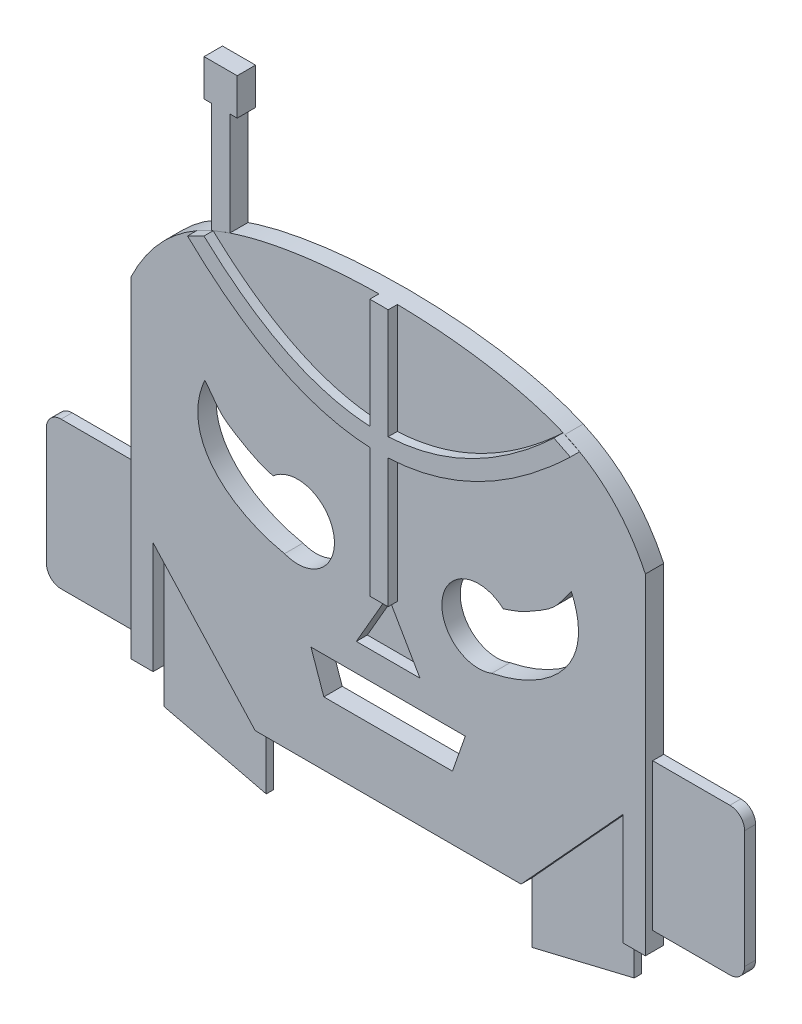
SolidWorks part; units mm, degrees
ref_plane "Alzado" through (0, 0, 0) normal (0, 0, 1) x (1, 0, 0)
ref_plane "Planta" through (0, 0, 0) normal (0, 1, 0) x (1, 0, 0)
ref_plane "Vista lateral" through (0, 0, 0) normal (1, 0, 0) x (0, 0, -1)
sketch "Croquis1" plane through (0, 0, 0) normal (0, 0, 1) x (1, 0, 0)
  line L0 (0, 0) -> (0, -7.1549) construction
  line L1 (-4.5362, -0.3549) -> (0, -0.3549) construction
  line L3 (-7, -2.6549) -> (-7, -11.6549)
  line L4 (-7, -11.6549) -> (7, -11.6549)
  line L5 (7, -2.6549) -> (7, -11.6549)
  line L6 (-7, -2.6549) -> (7, -11.6549) construction
  line L7 (-7, -11.6549) -> (7, -2.6549) construction
  line L12 (0, -0.3549) -> (4.5362, -0.3549) construction
  line L14 (-9.1, -7.1549) -> (-7, -7.1549)
  line L15 (-9.5, -7.5549) -> (-9.5, -10.7549)
  line L16 (-9.1, -11.1549) -> (-7, -11.1549)
  line L17 (-7, -7.1549) -> (-7, -11.1549)
  line L18 (-9.5, -7.1549) -> (-7, -11.1549) construction
  line L19 (-9.5, -11.1549) -> (-7, -7.1549) construction
  arc A0 (-9.5, -10.7549) -> (-9.1, -11.1549) centre (-9.1, -10.7549) ccw
  arc A1 (-9.1, -7.1549) -> (-9.5, -7.5549) centre (-9.1, -7.5549) ccw
  ellipse E0 centre (0, -1.6549) end of major axis (6.017, -1.6549) minor radius 1.9787 (5.4935, -0.8477) -> (-5.46, -0.8234) ccw
  spline S0 degree 2 poles (-7, -2.6549) (-6.1937, -0.9682) (-4.5362, -0.3549) knots 0 0 0 1 1 1
  spline S1 degree 2 poles (7, -2.6549) (6.1948, -0.9725) (4.5362, -0.3549) knots 0 0 0 1 1 1
  point P7 (8.2607, -8.8714)
  point P12 (-8.25, -9.1549)
  dimension "D2" = 0.4
  dimension "D7" = 3.4606
  dimension "D8" = 3.46
  dimension "D1" = 14
  dimension "D3" = 4
  dimension "D4" = 6.8
  dimension "D5" = 4.5362
  dimension "D6" = 5.5
  dimension "D9" = 0.5
  dimension "D10" = 2.5
  dimension "D11" = 9
extrude "Saliente-Extruir1" add sketch "Croquis1" along normal blind 0.5 contours L5 S1 E0 S0 L3 L4 | L14 A1 L15 A0 L16 L3
sketch "Croquis2" plane through (0, 0, 0.5) normal (0, 0, 1) x (1, 0, 0)
  line L0 (0, 0) -> (0, -3.1762) construction
  line L1 (-0.25, -6.6762) -> (0.25, -6.6762)
  line L2 (-0.25, -6.6762) -> (-0.25, 0.3238)
  line L3 (-0.25, 0.3238) -> (0.25, 0.3238)
  line L4 (0.25, -6.6762) -> (0.25, 0.3238)
  line L5 (-0.25, -6.6762) -> (0.25, 0.3238) construction
  line L6 (-0.25, 0.3238) -> (0.25, -6.6762) construction
  line L7 (-5.2093, -0.6681) -> (-4.7616, -0.4455) construction
  line L8 (0, -2.6762) -> (0, -3.1762) construction
  line L9 (4.7616, -0.4455) -> (5.2088, -0.6691) construction
  line L10 (-5.2093, -0.6681) -> (-4.7616, -0.4455)
  line L11 (4.7616, -0.4455) -> (5.2088, -0.6691)
  line L12 (-4.7616, -0.4455) -> (0, -0.4455) construction
  line L13 (0, -0.4455) -> (4.7616, -0.4455) construction
  ellipse E0 centre (0, -1.6549) end of major axis (6.017, -1.6549) minor radius 1.9787 (4.7173, -0.4266) -> (-4.8082, -0.4653) ccw construction
  parabola Q0 (-7, -2.6549) -> (-4.8082, -0.4653) focus (-4.4489, -2.6333) apex (-5.7288, -1.0195) construction
  parabola Q1 (7, -2.6549) -> (4.7173, -0.4266) focus (4.4505, -2.6489) apex (5.7448, -1.034) construction
  parabola Q4 (7, -2.6549) -> (4.7173, -0.4266) focus (4.4505, -2.6489) apex (5.7448, -1.034) construction
  parabola Q5 (7, -2.6549) -> (4.7173, -0.4266) focus (4.4505, -2.6489) apex (5.7448, -1.034) construction
  parabola Q6 (-7, -2.6549) -> (-4.8082, -0.4653) focus (-4.4489, -2.6333) apex (-5.7288, -1.0195) construction
  parabola Q7 (7, -2.6549) -> (4.7173, -0.4266) focus (4.4505, -2.6489) apex (5.7448, -1.034) construction
  parabola Q8 (7, -2.6549) -> (4.7173, -0.4266) focus (4.4505, -2.6489) apex (5.7448, -1.034) construction
  spline S0 degree 2 poles (-5.2093, -0.6681) (-0.0005, -5.6838) (5.2088, -0.6691) knots 0 0 0 1 1 1
  spline S1 degree 2 poles (-4.7616, -0.4455) (0, -4.907) (4.7616, -0.4455) knots 0 0 0 1 1 1
  point P0 (0, -3.1762)
  ellipse M11 centre (0, -1.6549) end of major axis (6.017, -1.6549) minor radius 1.9787 (4.7173, -0.4266) -> (-4.8082, -0.4653) ccw
  dimension "D1" = 0.5
  dimension "D2" = 0.5
  dimension "D3" = 0.5
  dimension "D4" = 0.5
  dimension "D5" = 7
extrude "Saliente-Extruir3" add sketch "Croquis2" along normal blind 0.25 contours S1 L10 S0 L2 | S1 L4 S0 L11 | S0 L2 L1 L4 | L2 S1 L4 M11 | S1 L2 S0 L4
sketch "Croquis3" plane through (0, 0, 0.5) normal (0, 0, 1) x (1, 0, 0)
  line L0 (-9.1, -7.1549) -> (-7, -7.1549) construction
  line L1 (-7, -11.1549) -> (-9.5, -11.1549)
  line L2 (-7, -11.1549) -> (-7, -7.1549)
  line L3 (-7, -7.1549) -> (-9.5, -7.1549)
  line L4 (-9.5, -11.1549) -> (-9.5, -7.1549)
  line L5 (-9.5, -7.5549) -> (-9.5, -10.7549) construction
extrude "Cortar-Extruir1" cut sketch "Croquis3" against normal blind 0.2
mirror "Simetría4" about plane through (0, 0, 0) normal (1, 0, 0) of "Cortar-Extruir1", "Saliente-Extruir1"
sketch "Croquis4" plane through (0, 0, 0.5) normal (0, 0, 1) x (1, 0, 0)
  line L0 (-0.25, -6.6762) -> (-0.25, -3.1704) construction
  circle A0 centre (-2.4616, -6.1519) radius 1
  spline S0 degree 3 poles (-2.8198, -7.0855) (-4.3185, -6.7814) (-5.7015, -5.6788) (-4.986, -4.0771) knots 0 0 0 0 1 1 1 1
  spline S1 degree 3 poles (-4.986, -4.0771) (-4.6566, -4.5316) (-4.5282, -4.7132) (-3.5882, -5.2683) (-3.516, -5.2764) (-3.1329, -5.4107) knots 0 0 0 0 0.376187 0.476187 1 1 1 1
  point P13 (-7, -2.6549)
  dimension "D1" = 2
  dimension "D2" = 2.2116
extrude "Cortar-Extruir2" cut sketch "Croquis4" against normal through all contours S1 S0 A0 | S1 A0
sketch "Croquis5" plane through (0, 0, 0.5) normal (0, 0, 1) x (1, 0, 0)
  line L0 (-0.25, -6.6762) -> (0.25, -6.6762) construction
  line L1 (0.866, -8.1762) -> (0, -6.6762)
  line L2 (0, -6.6762) -> (-0.866, -8.1762)
  line L3 (-0.866, -8.1762) -> (0.866, -8.1762)
  line L4 (-2.1, -8.9262) -> (2.1, -8.9262)
  line L5 (2.1, -8.9262) -> (1.75, -9.9262)
  line L6 (1.75, -9.9262) -> (-1.75, -9.9262)
  line L7 (-1.75, -9.9262) -> (-2.1, -8.9262)
  line L8 (0, -7.6762) -> (0, -8.9262) construction
  line L9 (0, -8.9262) -> (0, -9.9262) construction
  circle A0 centre (0, -7.6762) radius 0.5 construction
  point P12 (0, -8.9262)
  dimension "D1" = 1
  dimension "D2" = 1
  dimension "D3" = 4.2
  dimension "D4" = 2.25
  dimension "D5" = 3.5
extrude "Cortar-Extruir3" cut sketch "Croquis5" against normal blind 0.3
sketch "Croquis6" plane through (0, 0, 0.5) normal (0, 0, 1) x (1, 0, 0)
  line L0 (-4.8082, -0.4653) -> (-4.8082, 3.0347)
  line L1 (-4.8082, 3.0347) -> (-4.3082, 3.0347)
  line L2 (-4.3082, 3.0347) -> (-4.3082, -0.2736)
  line L4 (-5.0082, 3.5347) -> (-4.1082, 3.5347)
  line L5 (-5.0082, 3.5347) -> (-5.0082, 2.5347)
  line L6 (-5.0082, 2.5347) -> (-4.1082, 2.5347)
  line L7 (-4.1082, 3.5347) -> (-4.1082, 2.5347)
  line L8 (-5.0082, 3.5347) -> (-4.1082, 2.5347) construction
  line L9 (-5.0082, 2.5347) -> (-4.1082, 3.5347) construction
  ellipse E0 centre (0, -1.6549) end of major axis (6.017, -1.6549) minor radius 1.9787 (-0.25, 0.3221) -> (-4.8082, -0.4653) ccw construction
  spline S0 degree 2 poles (-4.8082, -0.4653) (-4.5873, -0.368) (-4.3082, -0.2736) knots 0 0 0 0.301705 0.301705 0.301705
  point P3 (-4.5582, 3.0347)
  dimension "D1" = 0.2
  dimension "D2" = 0.5
  dimension "D3" = 3.5
  dimension "D4" = 1
extrude "Saliente-Extruir4" add sketch "Croquis6" against normal up to surface (0.5 mm away) separate body contours L0 S0 L2 L6 | L7 L4 L5 L6 L0 L1 L2 | L0 L6 L2 L1 up to face at (0, -7.8228, 0)
sketch "Croquis7" plane through (0, 0, 0.5) normal (0, 0, 1) x (1, 0, 0)
  line L0 (-6.3968, -8.6165) -> (-6.3968, -12.6274)
  line L1 (-6.3968, -12.6274) -> (-3.6174, -13.2972)
  line L2 (-3.6174, -13.2972) -> (-3.6174, -11.6549)
  line L3 (-3.6174, -11.6549) -> (-6.3968, -8.6165)
  line L4 (-7, -11.6549) -> (7, -11.6549) construction
  dimension "D1" = 3.0384
  dimension "D2" = 0.6032
  dimension "D3" = 1.6422
extrude "Saliente-Extruir5" add sketch "Croquis7" against normal up to surface (0.5 mm away) up to face at (0, -7.8228, 0)
sketch "Croquis8" plane through (0, 0, 0.5) normal (0, 0, 1) x (1, 0, 0)
  line L0 (-6.3968, -12.6274) -> (-3.6174, -13.2972)
  line L1 (-3.6174, -13.2972) -> (-3.6174, -11.6549)
  line L2 (-3.6174, -11.6549) -> (-6.3968, -8.6165)
  line L3 (-6.3968, -8.6165) -> (-6.3968, -12.6274)
extrude "Cortar-Extruir4" cut sketch "Croquis8" against normal up to surface (0.3 mm away) up to face at (0, -9.4262, 0.2)
mirror "Simetría3" about plane through (0, 0, 0) normal (1, 0, 0) of "Cortar-Extruir4", "Saliente-Extruir5", "Cortar-Extruir2"
sketch "Croquis9" plane through (0, 0, 0.5) normal (0, 0, 1) x (1, 0, 0)
  line L0 (9.5, -7.5549) -> (9.5, -10.7549) construction
  line L1 (7, -7.1549) -> (9.5, -7.1549)
  line L2 (7, -7.1549) -> (7, -11.1549)
  line L3 (7, -11.1549) -> (9.5, -11.1549)
  line L4 (9.5, -7.1549) -> (9.5, -11.1549)
  line L5 (9.1, -11.1549) -> (7, -11.1549) construction
  line L6 (7, -2.6549) -> (7, -11.6549) construction
extrude "Cortar-Extruir5" [suppressed] cut sketch "Croquis9" against normal up to surface (0.2 mm away)
sketch "Croquis10" plane through (0, 0, 0.2) normal (0, 0, 1) x (1, 0, 0)
  line L4 (-1.75, -9.9262) -> (1.75, -9.9262)
  line L5 (1.75, -9.9262) -> (2.1, -8.9262)
  line L6 (2.1, -8.9262) -> (-2.1, -8.9262)
  line L7 (-2.1, -8.9262) -> (-1.75, -9.9262)
  line L8 (-1.75, -9.9262) -> (1.75, -9.9262)
  line L9 (1.75, -9.9262) -> (2.1, -8.9262)
  line L10 (2.1, -8.9262) -> (-2.1, -8.9262)
  line L11 (-2.1, -8.9262) -> (-1.75, -9.9262)
  dimension "D1" = 0
extrude "Cortar-Extruir6" cut sketch "Croquis10" against normal through all both and the other way through all
